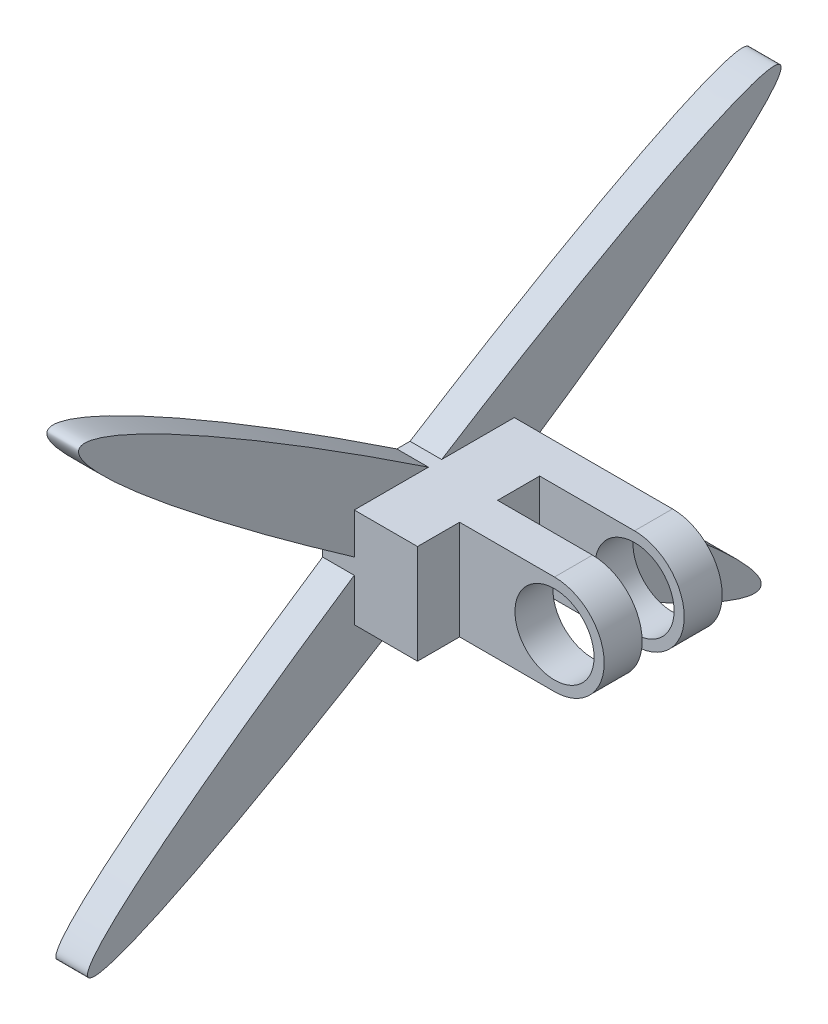
SolidWorks part; units mm, degrees
ref_plane "Plan de face" through (0, 0, 0) normal (0, 0, 1) x (1, 0, 0)
ref_plane "Plan de dessus" through (0, 0, 0) normal (0, 1, 0) x (1, 0, 0)
ref_plane "Plan de droite" through (0, 0, 0) normal (1, 0, 0) x (0, 0, -1)
sketch "Sketch2" plane through (0, 0, 0) normal (1, 0, 0) x (0, 0, -1)
  line L1 (0.9258, -7.85) -> (-1.1635, -7.85)
  line L2 (12.65, -1.4163) -> (12.65, 1.0899)
  line L3 (1.1635, 7.85) -> (-0.9258, 7.85)
  line L4 (-12.65, -1.0899) -> (-12.65, 1.4163)
  line L5 (20.219, -13.6818) -> (-20.219, 13.6818) construction
  line L6 (2.1483, 1.3773) -> (-20.5523, -13.1758) construction
  ellipse E0 centre (0, 0) end of major axis (-54.7207, -35.0806) minor radius 6 (12.65, 1.0899) -> (1.1635, 7.85) ccw
  ellipse E1 centre (0, 0) end of major axis (-56.1295, 37.9819) minor radius 6 (-0.9258, 7.85) -> (-12.65, 1.4163) ccw
  ellipse E2 centre (0, 0) end of major axis (54.7207, 35.0806) minor radius 6 (-12.65, -1.0899) -> (-1.1635, -7.85) ccw
  ellipse E3 centre (0, 0) end of major axis (-51.5636, 34.8344) minor radius 6.0072 (0.9258, -7.85) -> (12.65, -1.4163) ccw
  point P0 (0, 0)
  point P6 (50.8518, -34.3528)
  dimension "D1" = 15.7
  dimension "D2" = 25.3
  dimension "D3" = 12
  dimension "D4" = 12
  dimension "D5" = 130
  dimension "D6" = 130
  dimension "D7" = 67.7727
extrude "Boss-Extrude1" add sketch "Sketch2" along normal blind 5
sketch "Sketch3" plane through (5, 0, 0) normal (1, 0, 0) x (0, 0, -1)
  line L1 (12.65, -7.85) -> (-12.65, -7.85)
  line L2 (12.65, -7.85) -> (12.65, 7.85)
  line L3 (12.65, 7.85) -> (-12.65, 7.85)
  line L4 (-12.65, -7.85) -> (-12.65, 7.85)
  line L5 (12.65, -7.85) -> (-12.65, 7.85) construction
  line L6 (12.65, 7.85) -> (-12.65, -7.85) construction
  point P0 (0, 0)
  dimension "D1" = 25.3
  dimension "D2" = 15.7
extrude "Boss-Extrude2" add sketch "Sketch3" along normal blind 40
sketch "Sketch4" plane through (0, -7.85, 0) normal (0, -1, 0) x (1, 0, 0)
  line L17 (45, 12.65) -> (45, -12.65) construction
  line L18 (45, 12.65) -> (15, 12.65)
  line L19 (45, 12.65) -> (45, 6)
  line L20 (45, 6) -> (15, 6)
  line L21 (15, 12.65) -> (15, 6)
  line L22 (45, 0) -> (15, 0)
  line L23 (45, 0) -> (45, -6.65)
  line L24 (45, -6.65) -> (15, -6.65)
  line L25 (15, 0) -> (15, -6.65)
  dimension "D1" = 30
  dimension "D2" = 30
  dimension "D3" = 6
  dimension "D4" = 6.65
  dimension "D5" = 6.65
extrude "Cut-Extrude1" cut sketch "Sketch4" against normal blind 40
sketch "Sketch5" plane through (0, 0, 6) normal (0, 0, 1) x (1, 0, 0)
  line L0 (45, 7.85) -> (30, 7.85)
  line L1 (15, 7.85) -> (45, 7.85) construction
  line L2 (15, -7.85) -> (45, -7.85) construction
  line L3 (30, -7.85) -> (45, -7.85)
  line L4 (45, -7.85) -> (45, 7.85)
  arc A0 (30, 7.85) -> (30, -7.85) centre (30, 0) cw
extrude "Cut-Extrude2" cut sketch "Sketch5" against normal blind 36
sketch "Sketch6" plane through (0, 0, 6) normal (0, 0, 1) x (1, 0, 0)
  circle A0 centre (30, 0) radius 6.25
  dimension "D1" = 12.5
extrude "Cut-Extrude3" cut sketch "Sketch6" against normal blind 35
